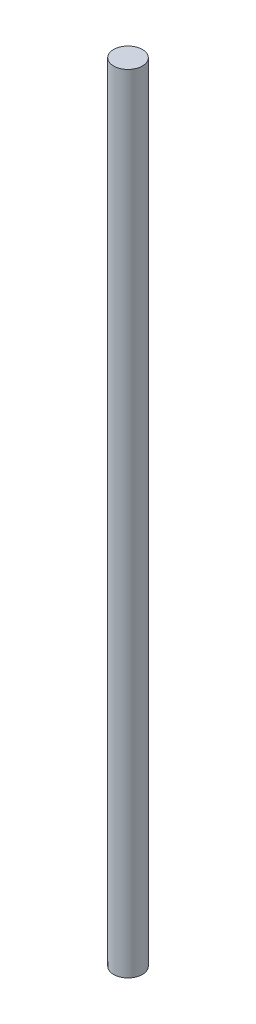
SolidWorks part; units mm, degrees
ref_plane "Front Plane" through (0, 0, 0) normal (0, 0, 1) x (1, 0, 0)
ref_plane "Top Plane" through (0, 0, 0) normal (0, 1, 0) x (1, 0, 0)
ref_plane "Right Plane" through (0, 0, 0) normal (1, 0, 0) x (0, 0, -1)
sketch "Sketch1" plane through (0, 0, 0) normal (0, 1, 0) x (1, 0, 0)
  circle A0 centre (0, 0) radius 6.35
  dimension "D1" = 12.7
extrude "Boss-Extrude1" add sketch "Sketch1" along normal blind 348.0003
equation "\"Diam tornillo\"=0.5"
equation "\"D1@Sketch1\"=\"Diam tornillo\""
equation "\"largo tornillo\"=13.7008"
equation "\"D1@Boss-Extrude1\"=\"largo tornillo\""
